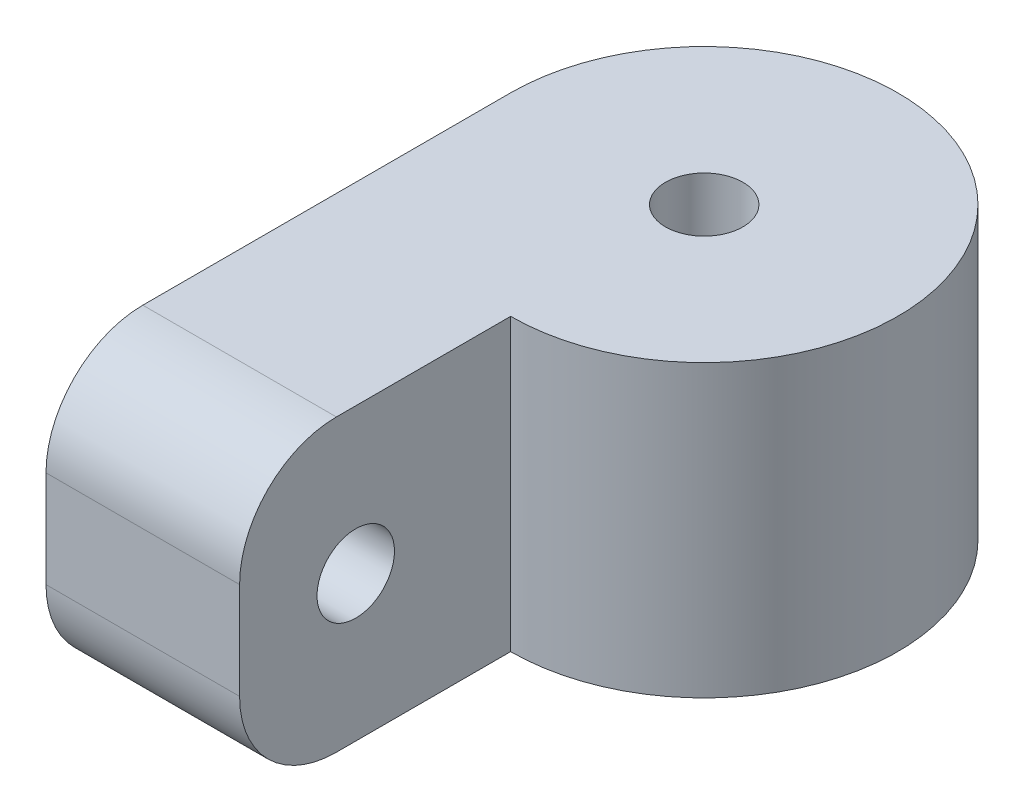
SolidWorks part; units mm, degrees
ref_plane "Ebene vorne" through (0, 0, 0) normal (0, 0, 1) x (1, 0, 0)
ref_plane "Ebene oben" through (0, 0, 0) normal (0, 1, 0) x (1, 0, 0)
ref_plane "Ebene rechts" through (0, 0, 0) normal (1, 0, 0) x (0, 0, -1)
sketch "Skizze1" plane through (0, 0, 0) normal (0, 1, 0) x (1, 0, 0)
  line L0 (0, 0) -> (0, -12)
  line L1 (0, -55) -> (0, 55) construction
  line L2 (0, -12) -> (10, -12)
  line L3 (10, -12) -> (10, 0)
  line L4 (-55, 0) -> (55, 0) construction
  line L5 (10, 0) -> (10, 12)
  line L6 (10, 12) -> (0, 12)
  line L7 (0, 12) -> (0, 0)
  line L8 (10, 12) -> (0, 12) construction
  circle A0 centre (10, 12) radius 10
  circle A1 centre (10, 12) radius 2
  dimension "D3" = 20
  dimension "D4" = 4
  dimension "D1" = 12
  dimension "D2" = 10
extrude "Aufsatz-Linear austragen1" add sketch "Skizze1" along normal blind 15 contours L6 A0 L5 | L5 A0 L6 | A0 L7 L0 L2 L3 L5
fillet "Verrundung1" radius 5 2 edges at (5, 0, 12) (5, 15, 12)
sketch "Skizze2" plane through (10, 0, 0) normal (1, 0, 0) x (0, 0, -1)
  line L0 (-12, 7.5) -> (0, 7.5) construction
  line L1 (-12, 10) -> (-12, 5) construction
  line L2 (0, 8.25) -> (0, -8.25) construction
  circle A0 centre (-6, 7.5) radius 2
  dimension "D1" = 4
extrude "Schnitt-Linear austragen1" cut sketch "Skizze2" against normal through all
